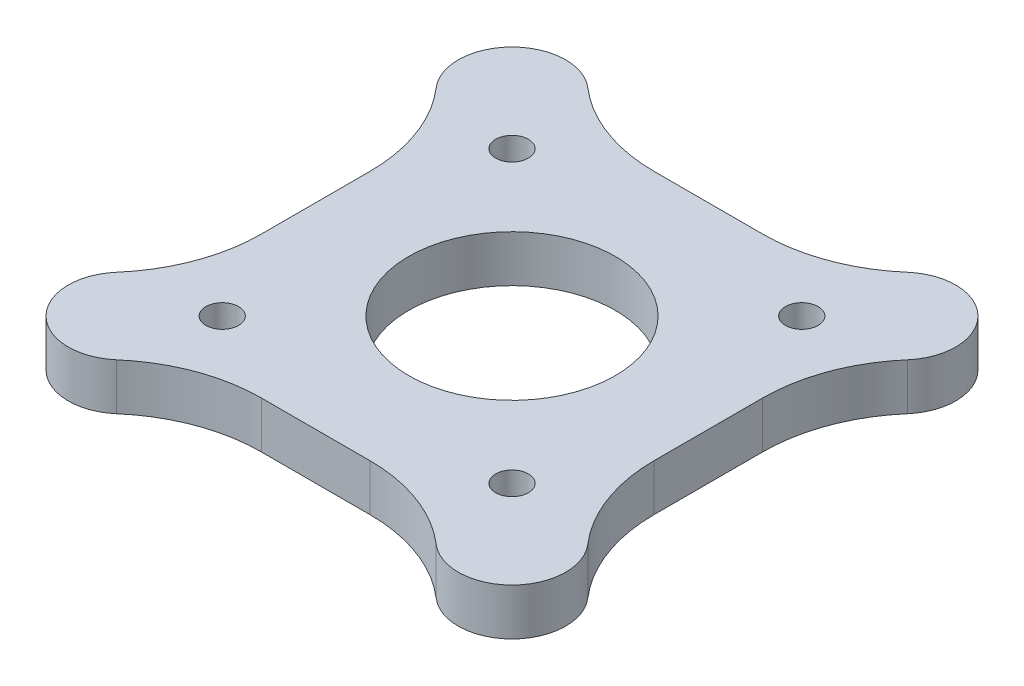
SolidWorks part; units mm, degrees
ref_plane "Front" through (0, 0, 0) normal (0, 0, 1) x (1, 0, 0)
ref_plane "Top" through (0, 0, 0) normal (0, 1, 0) x (1, 0, 0)
ref_plane "Right" through (0, 0, 0) normal (1, 0, 0) x (0, 0, -1)
sketch "草图1" plane through (0, 0, 0) normal (0, 1, 0) x (1, 0, 0)
  line L0 (-25.1989, 0) -> (25.3384, 0) construction
  line L1 (0, 24.0535) -> (0, -21.6423) construction
  line L3 (-21, -21) -> (21, -21)
  line L4 (-21, -21) -> (-21, 21)
  line L5 (-21, 21) -> (21, 21)
  line L6 (21, -21) -> (21, 21)
  line L7 (-21, -21) -> (21, 21) construction
  line L8 (-21, 21) -> (21, -21) construction
  circle A0 centre (0, 0) radius 11.05
  circle A1 centre (15.5, 15.5) radius 1.75
  circle A2 centre (15.5, -15.5) radius 1.75
  circle A3 centre (-15.5, -15.5) radius 1.75
  circle A4 centre (-15.5, 15.5) radius 1.75
  point P22 (0, 0)
  dimension "D1" = 22.1
  dimension "D4" = 15.5
  dimension "D6" = 3.5
  dimension "D2" = 42
  dimension "D3" = 42
  dimension "D5" = 4
extrude "凸台-拉伸1" add sketch "草图1" along normal blind 5
sketch "草图2" plane through (0, 0, 0) normal (0, 1, 0) x (1, 0, 0)
  line L0 (0, 0) -> (28.6077, -28.6077) construction
  line L1 (-5.8022, -21) -> (-21, -21)
  line L2 (-21, -21) -> (21, -21) construction
  line L3 (21, -5.8022) -> (21, -21)
  line L4 (21, -21) -> (5.8022, -21)
  line L5 (-21, -21) -> (-21, -5.8022)
  line L6 (-21, 5.8022) -> (-21, 21)
  line L7 (-21, 21) -> (-5.8022, 21)
  line L8 (5.8022, 21) -> (21, 21)
  line L9 (21, 21) -> (21, 5.8022)
  circle A0 centre (20.8597, -20.8597) radius 3.25 construction
  circle A1 centre (20.8597, -20.8597) radius 5.75 construction
  arc A2 (5.8022, -21) -> (17.0975, -25.2081) centre (5.8022, -38.2635) cw
  arc A3 (21, -5.8022) -> (25.2081, -17.0975) centre (38.2635, -5.8022) ccw
  arc A4 (25.2081, -17.0975) -> (17.0975, -25.2081) centre (20.8597, -20.8597) cw
  arc A5 (-5.8022, -21) -> (-17.0975, -25.2081) centre (-5.8022, -38.2635) ccw
  arc A6 (-17.0975, -25.2081) -> (-25.2081, -17.0975) centre (-20.8597, -20.8597) cw
  arc A7 (-21, -5.8022) -> (-25.2081, -17.0975) centre (-38.2635, -5.8022) cw
  arc A8 (-21, 5.8022) -> (-25.2081, 17.0975) centre (-38.2635, 5.8022) ccw
  arc A9 (-25.2081, 17.0975) -> (-17.0975, 25.2081) centre (-20.8597, 20.8597) cw
  arc A10 (-5.8022, 21) -> (-17.0975, 25.2081) centre (-5.8022, 38.2635) cw
  arc A11 (5.8022, 21) -> (17.0975, 25.2081) centre (5.8022, 38.2635) ccw
  arc A12 (17.0975, 25.2081) -> (25.2081, 17.0975) centre (20.8597, 20.8597) cw
  arc A13 (21, 5.8022) -> (25.2081, 17.0975) centre (38.2635, 5.8022) cw
  point P47 (0, 0)
  dimension "D1" = 6.5
  dimension "D3" = 2.5
  dimension "D2" = 29.5
extrude "凸台-拉伸2" add sketch "草图2" along normal blind 5
sketch "草图3" plane through (0, 0, 0) normal (0, -1, 0) x (1, 0, 0)
  line L0 (0, 0) -> (29.9149, 29.9149) construction
  line L1 (16.4973, 14.062) -> (22.6262, 18.3123)
  line L2 (-7.1544, 0) -> (30.4001, 0) construction
  circle A0 centre (20.8597, 20.8597) radius 3.1 construction
  circle A1 centre (20.8597, 20.8597) radius 5.75
  circle A2 centre (15.5, 15.5) radius 1.75 construction
  dimension "D1" = 6.2
  dimension "D3" = 45
  dimension "D2" = 29.5
